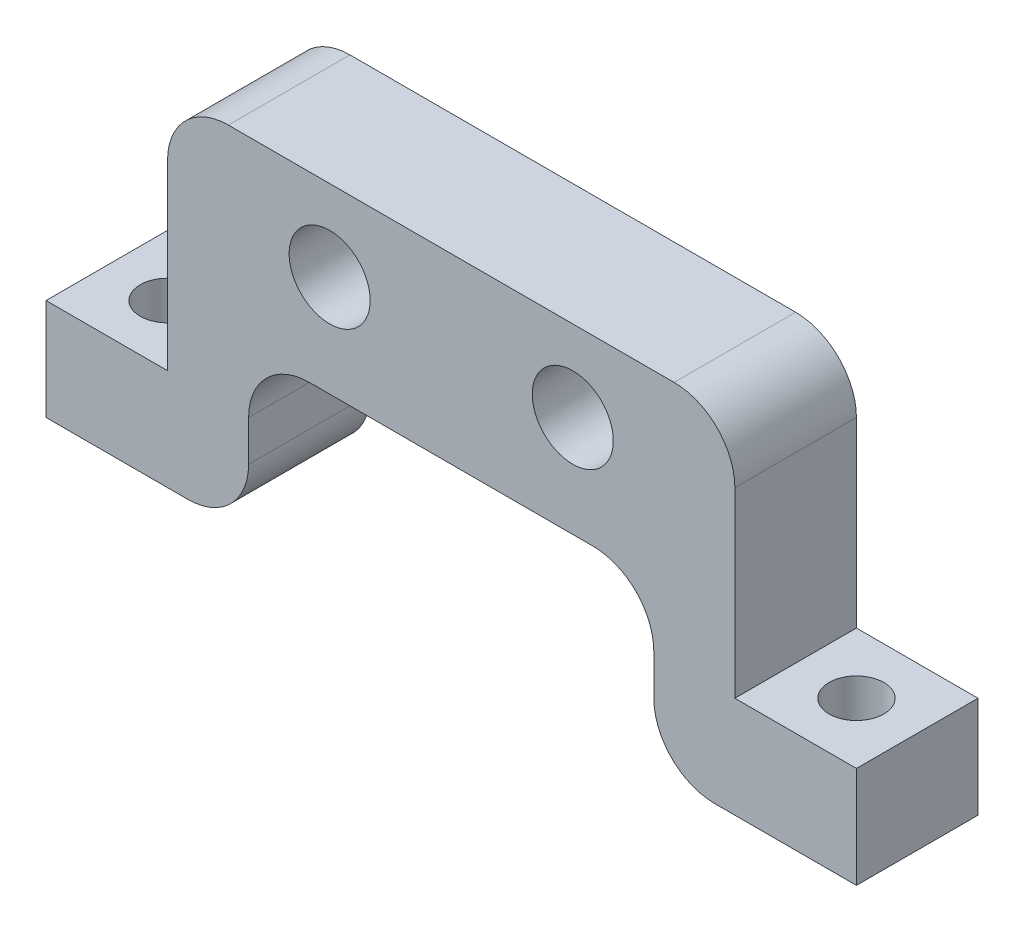
SolidWorks part; units mm, degrees
material "ABS"
ref_plane "前视基准面" through (0, 0, 0) normal (0, 0, 1) x (1, 0, 0)
ref_plane "上视基准面" through (0, 0, 0) normal (0, 1, 0) x (1, 0, 0)
ref_plane "右视基准面" through (0, 0, 0) normal (1, 0, 0) x (0, 0, -1)
sketch "草图1" plane through (0, 0, 0) normal (0, 0, 1) x (1, 0, 0)
  line L1 (-9, -8.5) -> (9, -8.5)
  line L2 (-9, -8.5) -> (-9, 8.5)
  line L3 (-9, 8.5) -> (9, 8.5)
  line L4 (9, -8.5) -> (9, 8.5)
  line L5 (-9, -8.5) -> (9, 8.5) construction
  line L6 (-9, 8.5) -> (9, -8.5) construction
  point P0 (0, 0)
  dimension "D2" = 17
  dimension "D1" = 18
extrude "凸台-拉伸1" add sketch "草图1" along normal blind 6
sketch "草图6" plane through (0, 0, 0) normal (0, 0, -1) x (-1, 0, 0)
  line L0 (0, 0) -> (0, -7.231) construction
  line L1 (-9, 8.5) -> (-14, 8.5)
  line L2 (-9, 8.5) -> (-9, -8.5)
  line L3 (-9, -8.5) -> (-20, -8.5)
  line L4 (-14, 8.5) -> (-14, -3.5)
  line L5 (20, -8.5) -> (20, -3.5)
  line L6 (14, -3.5) -> (20, -3.5)
  line L7 (-14, -3.5) -> (-20, -3.5)
  line L8 (-20, -8.5) -> (-20, -3.5)
  line L9 (14, 8.5) -> (14, -3.5)
  line L10 (9, -8.5) -> (20, -8.5)
  line L11 (9, 8.5) -> (9, -8.5)
  line L12 (9, 8.5) -> (14, 8.5)
  dimension "D1" = 5
  dimension "D2" = 6
  dimension "D3" = 5
  dimension "D4" = 17
extrude "凸台-拉伸2" add sketch "草图6" against normal blind 6
sketch "草图8" plane through (0, -3.5, 0) normal (0, 1, 0) x (1, 0, 0)
  line L0 (0, 5.6789) -> (0, -11.4986) construction
  line L2 (14, -3) -> (-15, -3) construction
  line L3 (14, -6) -> (14, 0) construction
  circle A0 centre (17, -3) radius 1.35
  circle A1 centre (-17, -3) radius 1.35
  dimension "D1" = 2.7
  dimension "D2" = 17
extrude "切除-拉伸4" cut sketch "草图8" against normal blind 5
sketch "草图9" plane through (0, 0, 6) normal (0, 0, 1) x (1, 0, 0)
  line L0 (0, 8.5) -> (0, -8.5) construction
  line L1 (14, 8.5) -> (-14, 8.5) construction
  line L2 (-20, -8.5) -> (20, -8.5) construction
  circle A0 centre (-6, 4.5) radius 2
  circle A3 centre (6, 4.5) radius 2
  dimension "D1" = 4
  dimension "D2" = 13
  dimension "D4" = 6
extrude "切除-拉伸5" cut sketch "草图9" against normal blind 10
sketch "草图10" plane through (0, 0, 6) normal (0, 0, 1) x (1, 0, 0)
  line L1 (-20, -8.5) -> (20, -8.5) construction
  line L2 (-10, -8.5) -> (10, -8.5)
  line L3 (-10, -8.5) -> (-10, -0.5)
  line L4 (-10, -0.5) -> (10, -0.5)
  line L5 (10, -8.5) -> (10, -0.5)
  line L6 (-10, -8.5) -> (10, -0.5) construction
  line L7 (-10, -0.5) -> (10, -8.5) construction
  point P4 (0, -4.5)
  dimension "D1" = 20
  dimension "D2" = 8
extrude "切除-拉伸6" cut sketch "草图10" against normal blind 10
fillet "圆角1" radius 3 6 edges at (14, 8.5, 3) (-14, 8.5, 3) (-10, -8.5, 3) (-10, -0.5, 3) (10, -0.5, 3) (10, -8.5, 3)
